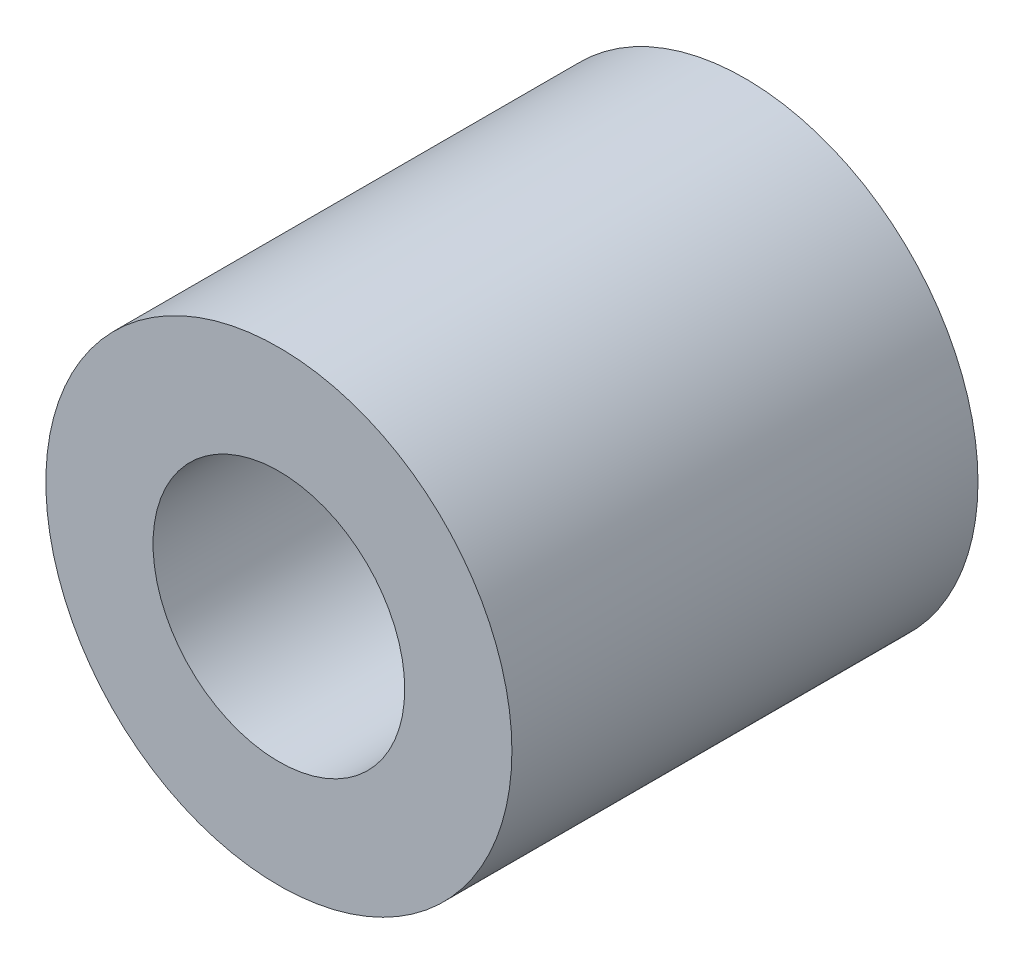
SolidWorks part; units mm, degrees
material "AISI 304"
ref_plane "正面" through (0, 0, 0) normal (0, 0, 1) x (1, 0, 0)
ref_plane "平面" through (0, 0, 0) normal (0, 1, 0) x (1, 0, 0)
ref_plane "右側面" through (0, 0, 0) normal (1, 0, 0) x (0, 0, -1)
sketch "ｽｹｯﾁ1" plane through (0, 0, 0) normal (0, 0, 1) x (1, 0, 0)
  circle A0 centre (0, 0) radius 2.5
  circle A1 centre (0, 0) radius 1.35
  dimension "D1" = 5
  dimension "D2" = 2.7
extrude "ﾎﾞｽ - 押し出し1" add sketch "ｽｹｯﾁ1" along normal blind 5
